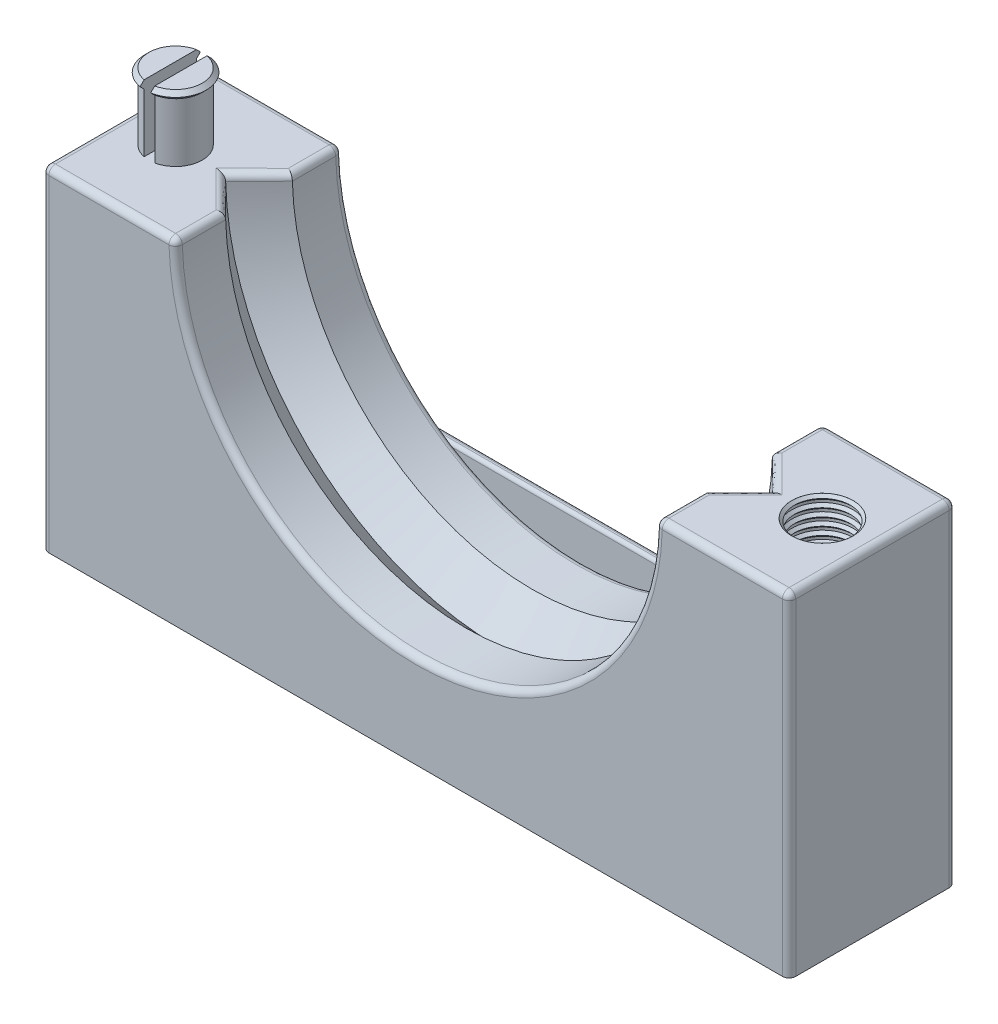
SolidWorks part; units mm, degrees
ref_plane "Front Plane" through (0, 0, 0) normal (0, 0, 1) x (1, 0, 0)
ref_plane "Top Plane" through (0, 0, 0) normal (0, 1, 0) x (1, 0, 0)
ref_plane "Right Plane" through (0, 0, 0) normal (1, 0, 0) x (0, 0, -1)
sketch "Sketch1" plane through (0, 0, 0) normal (0, 0, 1) x (1, 0, 0)
  line L0 (-35.56, 0) -> (35.56, 0)
  line L1 (35.56, 0) -> (35.56, 31.75)
  line L2 (35.56, 31.75) -> (22.86, 31.75)
  line L3 (-22.86, 31.75) -> (-35.56, 31.75)
  line L4 (-35.56, 31.75) -> (-35.56, 0)
  arc A0 (22.86, 31.75) -> (-22.86, 31.75) centre (0, 31.75) cw
  point P7 (0, 0)
  dimension "D2" = 22.86
  dimension "D1" = 31.75
  dimension "D3" = 12.7
extrude "Boss-Extrude1" add sketch "Sketch1" along normal blind 15.875
sketch "Sketch2" plane through (0, 31.75, 0) normal (0, 1, 0) x (1, 0, 0)
  line L0 (22.86, -11.1125) -> (26.035, -7.9375)
  line L2 (22.86, -15.875) -> (22.86, 0) construction
  line L3 (26.035, -7.9375) -> (22.86, -4.7625)
  line L4 (22.8654, -7.9375) -> (35.56, -7.9375) construction
  line L5 (22.86, -4.7625) -> (22.86, -11.1125)
  line L6 (35.56, -15.875) -> (35.56, 0) construction
  line L7 (0, 0) -> (0, -23.6383) construction
  dimension "D1" = 6.35
  dimension "D2" = 3.175
revolve "Cut-Revolve1" cut sketch "Sketch2" angle 360 about L7
sketch "Sketch6" plane through (0, 31.75, 0) normal (0, 1, 0) x (1, 0, 0)
  line L0 (26.035, -7.9375) -> (35.56, -7.9375) construction
  line L1 (35.56, -15.875) -> (35.56, 0) construction
  circle A0 centre (30.7975, -7.9375) radius 2.921
  dimension "D1" = 5.842
extrude "Cut-Extrude2" cut sketch "Sketch6" against normal blind 9.525
sketch "Sketch11" plane through (0, 31.75, 0) normal (0, 1, 0) x (1, 0, 0)
  line L0 (26.035, -7.9375) -> (35.56, -7.9375) construction
  line L1 (35.56, -15.875) -> (35.56, 0) construction
ref_plane "Plane1" through (0, 0, 7.9375) normal (0, 0, 1) x (1, 0, 0)
sketch "Sketch15" plane through (0, 0, 7.9375) normal (0, 0, 1) x (1, 0, 0)
  line L0 (-33.3375, 31.75) -> (-33.3375, 37.338)
  line L1 (-22.86, 31.75) -> (-35.56, 31.75) construction
  line L2 (-33.3375, 37.338) -> (-33.7185, 37.719)
  line L3 (-33.7185, 37.719) -> (-33.3375, 38.1)
  line L4 (-33.3375, 38.1) -> (-30.7975, 38.1)
  line L5 (-30.7975, 38.1) -> (-30.7975, 31.75)
  line L6 (-30.7975, 31.75) -> (-33.3375, 31.75)
  line L7 (-35.56, 31.75) -> (-35.56, 0) construction
  line L8 (-33.3375, 38.1) -> (-33.3375, 37.338) construction
  line L9 (-26.035, 31.75) -> (-35.56, 31.75) construction
  dimension "D1" = 2.54
  dimension "D3" = 6.35
  dimension "D4" = 90
  dimension "D5" = 2.921
revolve "Revolve2" add sketch "Sketch15" angle 360 about L5
sketch "Sketch12" plane through (0, 0, 7.9375) normal (0, 0, 1) x (1, 0, 0)
  line L0 (30.7975, 31.75) -> (30.7975, 26.6144) construction
  line L1 (26.035, 31.75) -> (35.56, 31.75) construction
  line L2 (27.8765, 30.48) -> (28.1305, 30.734)
  line L3 (27.8765, 31.242) -> (28.1305, 31.496)
  line L4 (28.1305, 31.496) -> (27.8765, 31.75)
  line L5 (27.8765, 31.75) -> (27.8765, 31.242)
  line L6 (30.7975, 31.75) -> (27.8765, 31.75) construction
  line L7 (28.1305, 30.734) -> (27.8765, 30.988)
  line L8 (27.8765, 30.988) -> (27.8765, 30.48)
  line L9 (27.8765, 29.718) -> (28.1305, 29.972)
  line L10 (28.1305, 29.972) -> (27.8765, 30.226)
  line L11 (27.8765, 30.226) -> (27.8765, 29.718)
  line L12 (27.8765, 28.956) -> (28.1305, 29.21)
  line L13 (28.1305, 29.21) -> (27.8765, 29.464)
  line L14 (27.8765, 29.464) -> (27.8765, 28.956)
  line L15 (27.8765, 28.194) -> (28.1305, 28.448)
  line L16 (28.1305, 28.448) -> (27.8765, 28.702)
  line L17 (27.8765, 28.702) -> (27.8765, 28.194)
  line L18 (27.8765, 27.432) -> (28.1305, 27.686)
  line L19 (28.1305, 27.686) -> (27.8765, 27.94)
  line L20 (27.8765, 27.94) -> (27.8765, 27.432)
  line L21 (27.8765, 26.67) -> (28.1305, 26.924)
  line L22 (28.1305, 26.924) -> (27.8765, 27.178)
  line L23 (27.8765, 27.178) -> (27.8765, 26.67)
  line L24 (27.8765, 25.908) -> (28.1305, 26.162)
  line L25 (28.1305, 26.162) -> (27.8765, 26.416)
  line L26 (27.8765, 26.416) -> (27.8765, 25.908)
  line L27 (27.8765, 25.146) -> (28.1305, 25.4)
  line L28 (28.1305, 25.4) -> (27.8765, 25.654)
  line L29 (27.8765, 25.654) -> (27.8765, 25.146)
  line L30 (27.8765, 24.384) -> (28.1305, 24.638)
  line L31 (28.1305, 24.638) -> (27.8765, 24.892)
  line L32 (27.8765, 24.892) -> (27.8765, 24.384)
  line L33 (27.8765, 23.622) -> (28.1305, 23.876)
  line L34 (28.1305, 23.876) -> (27.8765, 24.13)
  line L35 (27.8765, 24.13) -> (27.8765, 23.622)
  line L36 (27.8765, 22.86) -> (28.1305, 23.114)
  line L37 (28.1305, 23.114) -> (27.8765, 23.368)
  line L38 (27.8765, 23.368) -> (27.8765, 22.86)
  line L39 (27.8765, 22.098) -> (28.1305, 22.352)
  line L40 (28.1305, 22.352) -> (27.8765, 22.606)
  line L41 (27.8765, 22.606) -> (27.8765, 22.098)
  line L42 (27.8765, 21.336) -> (28.1305, 21.59)
  line L43 (28.1305, 21.59) -> (27.8765, 21.844)
  line L44 (27.8765, 21.844) -> (27.8765, 21.336)
  line L45 (27.8765, 20.574) -> (28.1305, 20.828)
  line L46 (28.1305, 20.828) -> (27.8765, 21.082)
  line L47 (27.8765, 21.082) -> (27.8765, 20.574)
  line L48 (27.8765, 19.812) -> (28.1305, 20.066)
  line L49 (28.1305, 20.066) -> (27.8765, 20.32)
  line L50 (27.8765, 20.32) -> (27.8765, 19.812)
  line L51 (27.8765, 19.05) -> (28.1305, 19.304)
  line L52 (28.1305, 19.304) -> (27.8765, 19.558)
  line L53 (27.8765, 19.558) -> (27.8765, 19.05)
  line L54 (27.8765, 18.288) -> (28.1305, 18.542)
  line L55 (28.1305, 18.542) -> (27.8765, 18.796)
  line L56 (27.8765, 18.796) -> (27.8765, 18.288)
  line L57 (27.8765, 17.526) -> (28.1305, 17.78)
  line L58 (28.1305, 17.78) -> (27.8765, 18.034)
  line L59 (27.8765, 18.034) -> (27.8765, 17.526)
  line L60 (27.8765, 16.764) -> (28.1305, 17.018)
  line L61 (28.1305, 17.018) -> (27.8765, 17.272)
  line L62 (27.8765, 17.272) -> (27.8765, 16.764)
  dimension "D1" = 2.921
  dimension "D2" = 0.508
  dimension "D3" = 90
  dimension "D4" = 20
revolve "Revolve1" add sketch "Sketch12" angle 360 about L0
sketch "Sketch16" plane through (0, 38.1, 0) normal (0, 1, 0) x (1, 0, 0)
  line L1 (-31.3055, -13.5293) -> (-30.2895, -13.5293)
  line L2 (-31.3055, -13.5293) -> (-31.3055, -2.3457)
  line L3 (-31.3055, -2.3457) -> (-30.2895, -2.3457)
  line L4 (-30.2895, -13.5293) -> (-30.2895, -2.3457)
  line L5 (-31.3055, -13.5293) -> (-30.2895, -2.3457) construction
  line L6 (-31.3055, -2.3457) -> (-30.2895, -13.5293) construction
  point P0 (-30.7975, -7.9375)
  dimension "D1" = 1.016
extrude "Cut-Extrude3" cut sketch "Sketch16" against normal up to surface (6.35 mm away) up to face at (-30.7975, 31.75, 10.4775)
sketch "Sketch17" plane through (0, 0, 0) normal (0, 1, 0) x (1, 0, 0)
  line L1 (-19.05, -4.7244) -> (19.05, -4.7244)
  line L2 (-19.05, -4.7244) -> (-19.05, 4.7244)
  line L3 (-19.05, 4.7244) -> (19.05, 4.7244)
  line L4 (19.05, -4.7244) -> (19.05, 4.7244)
  line L5 (-19.05, -4.7244) -> (19.05, 4.7244) construction
  line L6 (-19.05, 4.7244) -> (19.05, -4.7244) construction
  point P0 (0, 0)
  dimension "D1" = 9.4488
  dimension "D2" = 38.1
extrude "Boss-Extrude2" add sketch "Sketch17" along normal blind 1.5875
sketch "Sketch18" plane through (0, 0, -4.7244) normal (0, 0, -1) x (-1, 0, 0)
  line L0 (-19.05, 1.5875) -> (-19.05, 0) construction
  line L1 (19.05, 0) -> (-19.05, 0)
  line L2 (19.05, 0) -> (19.05, 7.62)
  line L3 (19.05, 7.62) -> (-19.05, 7.62)
  line L4 (-19.05, 0) -> (-19.05, 7.62)
  dimension "D1" = 7.62
extrude "Boss-Extrude3" add sketch "Sketch18" along normal blind 0.8
fillet "Fillet1" radius 0.635 20 edges at (35.56, 15.875, 0) (35.56, 15.875, 15.875) (0, 8.89, 0) (-22.86, 31.75, 2.3813) (-22.86, 31.75, 13.4937) (22.86, 31.75, 13.4937) (22.86, 31.75, 2.3812) (24.4475, 31.75, 6.35) (24.4475, 31.75, 9.525) (29.21, 31.75, 15.875) (35.56, 31.75, 7.9375) (29.21, 31.75, 0) (-29.21, 31.75, 0) (-24.4475, 31.75, 6.35) (-24.4475, 31.75, 9.525) (0, 8.89, 15.875) (-29.21, 31.75, 15.875) (-35.56, 15.875, 15.875) (-35.56, 31.75, 7.9375) (-35.56, 15.875, 0)
fillet "Fillet2" radius 0.3175 11 edges at (19.05, 0.7937, 0) (0, 1.5875, 0) (-19.05, 0.7937, 0) (0, 7.62, -4.7244) (0, 7.62, -5.5244) (19.05, 3.81, -5.5244) (-19.05, 3.81, -5.5244)
